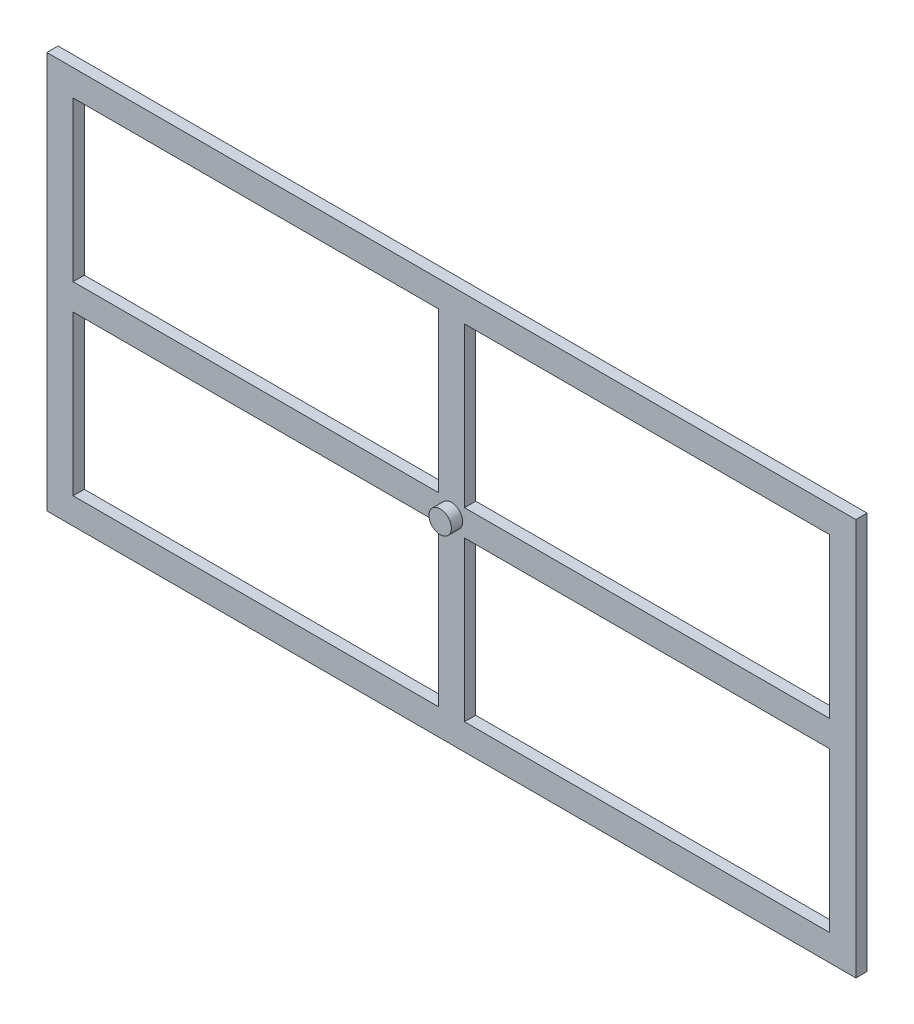
SolidWorks part; units mm, degrees
ref_plane "Plano frontal" through (0, 0, 0) normal (0, 0, 1) x (1, 0, 0)
ref_plane "Plano superior" through (0, 0, 0) normal (0, 1, 0) x (1, 0, 0)
ref_plane "Plano direito" through (0, 0, 0) normal (1, 0, 0) x (0, 0, -1)
sketch "Esboço1" plane through (0, 0, 0) normal (0, 0, 1) x (1, 0, 0)
  line L0 (-132.3546, 42.7056) -> (83.6454, 42.7056)
  line L1 (-132.3546, 42.7056) -> (-132.3546, -63.2944)
  line L2 (-132.3546, -63.2944) -> (83.6454, -63.2944)
  line L3 (83.6454, 42.7056) -> (83.6454, -63.2944)
  line L4 (-125.3546, 35.7056) -> (-27.8546, 35.7056)
  line L5 (-125.3546, 35.7056) -> (-125.3546, -6.7944)
  line L6 (-125.3546, -6.7944) -> (-27.8546, -6.7944)
  line L7 (-27.8546, 35.7056) -> (-27.8546, -6.7944)
  line L8 (-20.8546, 35.7056) -> (76.6454, 35.7056)
  line L9 (-20.8546, 35.7056) -> (-20.8546, -6.7944)
  line L10 (-20.8546, -6.7944) -> (76.6454, -6.7944)
  line L11 (76.6454, 35.7056) -> (76.6454, -6.7944)
  line L12 (-20.8546, -13.7944) -> (76.6454, -13.7944)
  line L13 (-20.8546, -13.7944) -> (-20.8546, -56.2944)
  line L14 (-20.8546, -56.2944) -> (76.6454, -56.2944)
  line L15 (76.6454, -13.7944) -> (76.6454, -56.2944)
  line L16 (-27.8546, -56.2944) -> (-125.3546, -56.2944)
  line L17 (-27.8546, -56.2944) -> (-27.8546, -13.7944)
  line L18 (-27.8546, -13.7944) -> (-125.3546, -13.7944)
  line L19 (-125.3546, -56.2944) -> (-125.3546, -13.7944)
extrude "Ressalto-extrusão1" add sketch "Esboço1" along normal blind 3
sketch "Esboço2" plane through (0, 0, 3) normal (0, 0, 1) x (1, 0, 0)
  line L0 (-27.8546, -13.7944) -> (-20.8546, -6.7944) construction
  circle A0 centre (-24.3546, -10.2944) radius 3
extrude "Ressalto-extrusão2" add sketch "Esboço2" along normal blind 3
sketch "Esboço3" plane through (0, 0, 0) normal (0, 0, -1) x (-1, 0, 0)
  circle A0 centre (-79.6454, 38.7056) radius 2
  circle A1 centre (128.3546, 38.7056) radius 2
  circle A2 centre (-79.6454, -59.2944) radius 2
  circle A3 centre (128.3546, -59.2944) radius 2
extrude "Corte-extrusão1" cut sketch "Esboço3" against normal blind 1
